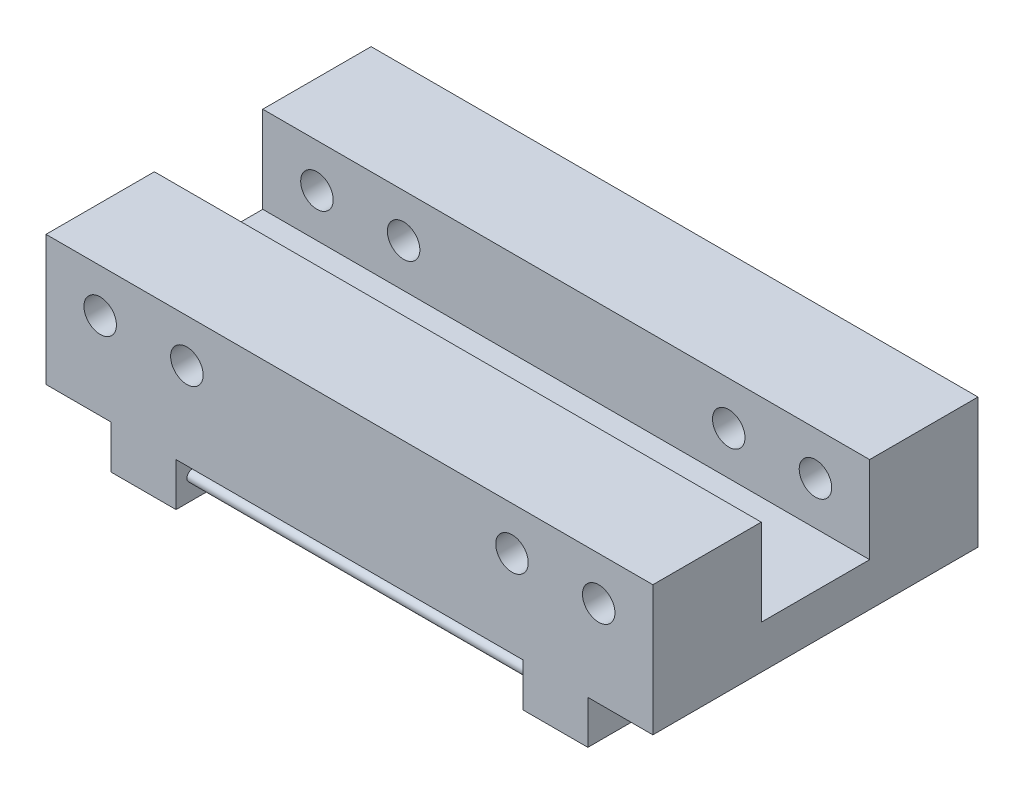
SolidWorks part; units mm, degrees
ref_plane "Front Plane" through (0, 0, 0) normal (0, 0, 1) x (1, 0, 0)
ref_plane "Top Plane" through (0, 0, 0) normal (0, 1, 0) x (1, 0, 0)
ref_plane "Right Plane" through (0, 0, 0) normal (1, 0, 0) x (0, 0, -1)
sketch "Sketch1" plane through (0, 0, 0) normal (0, 1, 0) x (1, 0, 0)
  line L1 (0, 0) -> (-280, 0)
  line L2 (0, 0) -> (0, 150)
  line L3 (0, 150) -> (-280, 150)
  line L4 (-280, 0) -> (-280, 150)
  dimension "D1" = 280
  dimension "D2" = 150
extrude "Boss-Extrude1" add sketch "Sketch1" against normal blind 20
sketch "Sketch2" plane through (0, -20, 0) normal (0, -1, 0) x (1, 0, 0)
  line L0 (-280, 0) -> (0, 0) construction
  line L1 (-250, 0) -> (-220, 0)
  line L2 (-250, 0) -> (-250, -30)
  line L3 (-250, -30) -> (-220, -30)
  line L4 (-220, 0) -> (-220, -30)
  line L5 (-280, -150) -> (-280, 0) construction
  dimension "D1" = 30
  dimension "D2" = 30
  dimension "D3" = 30
extrude "Boss-Extrude2" add sketch "Sketch2" along normal blind 20
ref_plane "Plane1" through (0, 0, -75) normal (0, 0, -1) x (-1, 0, 0)
ref_plane "Plane2" through (-140, 0, 0) normal (-1, 0, 0) x (0, 0, 1)
mirror "Mirror1" about plane through (-140, 0, 0) normal (-1, 0, 0) of "Boss-Extrude2" second plane through (0, 0, -75) second plane normal (0, 0, -1)
sketch "Sketch3" plane through (-220, 0, 0) normal (1, 0, 0) x (0, 0, -1)
  line L0 (0, -40) -> (0, -20) construction
  line L1 (30, -40) -> (30, -20) construction
  line L2 (0, -40) -> (30, -40) construction
  line L3 (0, -20) -> (150, -20) construction
  circle A0 centre (7.5, -30) radius 2.5
  circle A1 centre (22.5, -30) radius 2.5
  dimension "D1" = 5
  dimension "D2" = 5
  dimension "D3" = 7.5
  dimension "D4" = 7.5
  dimension "D5" = 10
  dimension "D6" = 10
extrude "Boss-Extrude3" add sketch "Sketch3" along normal blind 160
mirror "Mirror2" about plane through (0, 0, -75) normal (0, 0, -1) of "Boss-Extrude3"
sketch "Sketch7" plane through (0, 0, 0) normal (0, 1, 0) x (1, 0, 0)
  line L0 (0, 0) -> (0, 150) construction
  line L1 (-280, 150) -> (0, 150)
  line L2 (-280, 150) -> (-280, 100)
  line L3 (-280, 100) -> (0, 100)
  line L4 (0, 150) -> (0, 100)
  dimension "D1" = 50
extrude "Boss-Extrude5" add sketch "Sketch7" along normal blind 40
mirror "Mirror4" about plane through (0, 0, -75) normal (0, 0, -1) of "Boss-Extrude5"
sketch "Sketch8" plane through (0, 0, -150) normal (0, 0, -1) x (-1, 0, 0)
  line L0 (0, 40) -> (280, 40) construction
  line L1 (0, -20) -> (0, 40) construction
  line L2 (280, -20) -> (280, 40) construction
  circle A0 centre (25, 20) radius 7.5
  circle A1 centre (65, 20) radius 7.5
  circle A2 centre (215, 20) radius 7.5
  circle A3 centre (255, 20) radius 7.5
  dimension "D1" = 15
  dimension "D2" = 15
  dimension "D3" = 15
  dimension "D4" = 15
  dimension "D5" = 20
  dimension "D6" = 20
  dimension "D7" = 20
  dimension "D8" = 20
  dimension "D9" = 25
  dimension "D10" = 40
  dimension "D11" = 40
  dimension "D12" = 25
extrude "Cut-Extrude1" cut sketch "Sketch8" against normal through all
